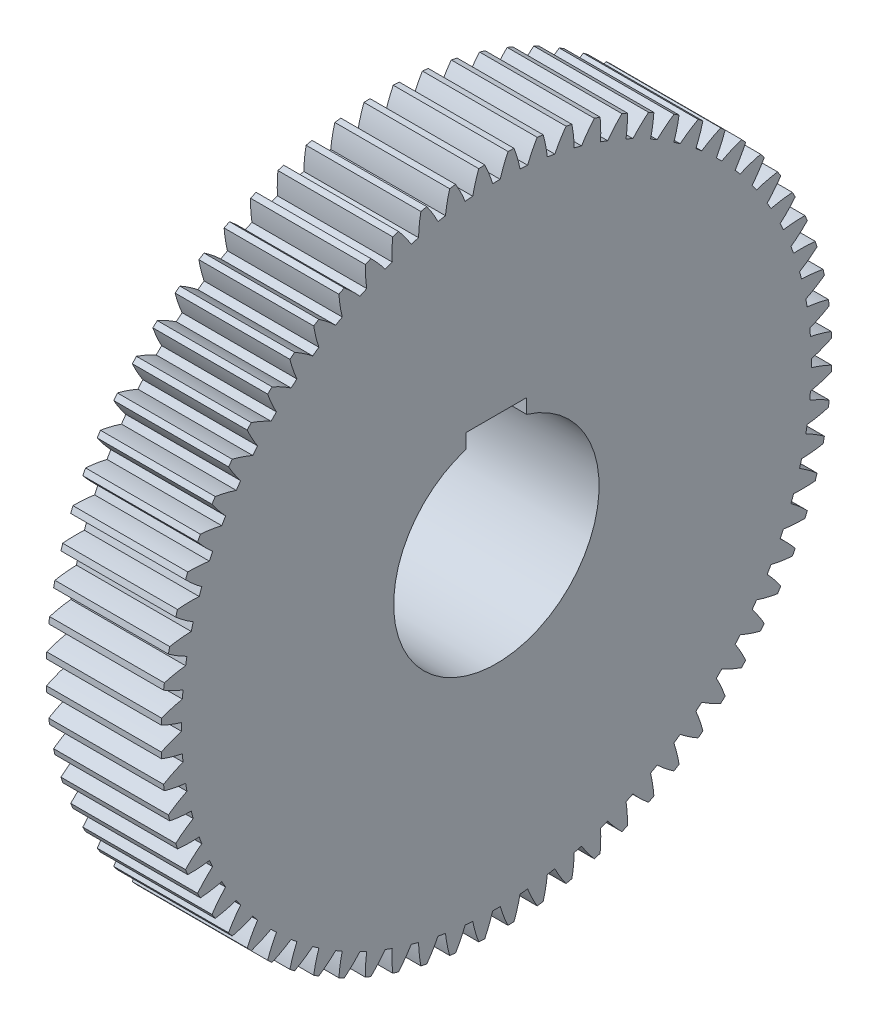
SolidWorks part; units mm, degrees
ref_plane "Plane1" through (0, 0, 0) normal (0, 0, 1) x (1, 0, 0)
ref_plane "Plane2" through (0, 0, 0) normal (0, 1, 0) x (1, 0, 0)
ref_plane "Plane3" through (0, 0, 0) normal (1, 0, 0) x (0, 0, -1)
sketch "HoldingSke" plane through (0, 0, 0) normal (0, 1, 0) x (1, 0, 0)
  line L0 (0, 0) -> (0.103, -0.317)
  line L1 (-15, 0) -> (100, 0) construction
  line L2 (0, 0) -> (-2.1039, 2.3779)
  line L3 (0, 0) -> (-11.863, 4.5341)
  line L4 (0, 0) -> (2.6687, 8.2133)
  line L5 (0, 0) -> (-58.0911, -21.6663)
  line L6 (0, 0) -> (-31.5006, -21.2535)
  line L7 (-2.1039, 2.3779) -> (11.2416, 62.9246)
  line L8 (-76.2, 54.61) -> (-71.3, 54.61)
  line L9 (-71.009, 38.7566) -> (-53.1078, 45.2721)
  line L10 (-76.2, 71.12) -> (104.1128, 71.12)
  line L11 (0, 0) -> (-38, 0)
  line L12 (-76.2, 101.6) -> (-76.093, 101.6)
  line L13 (24.9733, 27.94) -> (52.9518, 28.4284)
  line L14 (24.9733, 27.94) -> (24.9743, 27.94)
  line L15 (24.9733, 27.94) -> (100.4006, 29.5858)
  line L16 (-63.627, -3) -> (-12.827, -3)
  circle A0 centre (0, 0) radius 35
  circle A1 centre (0, 0) radius 42.5
  circle A2 centre (0, 0) radius 42.5
  circle A3 centre (0, 0) radius 35
  dimension "MHD" = 85
  dimension "Hub_dia" = 85
  dimension "Bore" = 70
  dimension "MBD" = 70
  dimension "Num_teeth" = 72
  dimension "Pitch" = 0.3333
  dimension "Overall_len" = 62
  dimension "Show_teeth" = 72
  dimension "Thickness" = 38
  dimension "OAL" = 62.0001
  dimension "T_dim" = 4.9
  dimension "Ap" = 20
  dimension "H" = 19.05
  dimension "Pitch_radius" = 180.3128
  dimension "Width" = 38
  dimension "Backlash" = 0.107
  dimension "Addendum_fac" = 1
  dimension "Dedendum_fac" = 1.25
  dimension "Clearance_fac" = 0.25
  dimension "Dedendum_add" = 0.001
  dimension "Module" = 3
sketch "BasProSke" plane through (0, 0, 0) normal (0, 1, 0) x (1, 0, 0)
  line L0 (-10, 0) -> (60, 0) construction
  line L1 (0, 0) -> (0, 111)
  line L2 (0, 0) -> (38, 0)
  line L3 (38, 0) -> (38, 111)
  line L4 (38, 111) -> (0, 111)
  dimension "Thickness" = 38
  dimension "Diameter" = 222
revolve "Base-Revolve" add sketch "BasProSke" angle 360 about L0
sketch "TooCutSke" plane through (0, 0, 0) normal (1, 0, 0) x (0, 0, -1)
  line L1 (0, 0) -> (0, 107) construction
  line L2 (0, 0) -> (-2.5433, 107.9701) construction
  line L3 (0, 0) -> (-9.4199, 215.7509) construction
  line L4 (-2.5433, 107.9701) -> (-4.7099, 107.8755) construction
  arc A0 (1.2601, 104.2414) -> (-1.2601, 104.2414) centre (0, 0) ccw
  arc A1 (3.8595, 110.9583) -> (-3.8595, 110.9583) centre (0, 0) ccw
  circle A2 centre (0, 0) radius 108 construction
  circle A3 centre (0, 0) radius 101.4868 construction
  arc A4 (-1.2601, 104.2414) -> (-3.8595, 110.9583) centre (-42.708, 92.063) ccw
  arc A5 (3.8595, 110.9583) -> (1.2601, 104.2414) centre (42.708, 92.063) ccw
  dimension "Root_dia" = 208.498
  dimension "Overcut_dia" = 222.0508
  dimension "Pitch_dia" = 216
  dimension "Base_dia" = 202.9736
  dimension "Flank_rad" = 43.2
  dimension "Half_ang" = 2.5
  dimension "Half_CT" = 2.1688
extrude "ToothCut" cut sketch "TooCutSke" along normal through all
fillet "Breaks" [suppressed] radius 0.06
fillet "RootFillets" [suppressed] radius 0.751
pattern_circular "TeethCuts" count 72 over 360 about axis through (0, 0, 0) along (1, 0, 0) of "ToothCut", "RootFillets", "Breaks"
sketch "HubNeaOneSke" plane through (0, 0, 0) normal (-1, 0, 0) x (0, 0, 1)
  circle A0 centre (0, 0) radius 42.5
  dimension "Diameter" = 85
extrude "HubNearOne" add sketch "HubNeaOneSke" along normal blind 24.0001
sketch "HubNeaBotSke" plane through (0, 0, 0) normal (-1, 0, 0) x (0, 0, 1)
  circle A0 centre (0, 0) radius 42.5
  dimension "Diameter" = 85
extrude "HubNearBoth" [suppressed] add sketch "HubNeaBotSke" along normal blind 12
ref_plane "FarPln" through (38, 0, 0) normal (1, 0, 0) x (0, 0, -1)
sketch "HubFarSke" plane through (38, 0, 0) normal (1, 0, 0) x (0, 0, -1)
  circle A0 centre (0, 0) radius 42.5
  dimension "Diameter" = 85
extrude "HubFar" [suppressed] add sketch "HubFarSke" along normal blind 12
sketch "BorSke" plane through (0, 0, 0) normal (1, 0, 0) x (0, 0, -1)
  circle A0 centre (0, 0) radius 34
  dimension "Diameter" = 68
extrude "Bore" cut sketch "BorSke" along normal mid plane 124.0001
sketch "KeySke" plane through (0, 0, 0) normal (1, 0, 0) x (0, 0, -1)
  line L0 (-10, 0) -> (-10, 37.3)
  line L1 (-10, 37.3) -> (10, 37.3)
  line L2 (10, 37.3) -> (10, 0)
  line L3 (0, 0) -> (0, 34) construction
  line L4 (-10, 0) -> (10, 0)
  dimension "Offset" = 37.3
  dimension "Width" = 20
extrude "Keyway" cut sketch "KeySke" along normal mid plane 124.0001
pattern_circular "Keyway2" [suppressed] count 2 every 90 about axis through (-10, 0, 0) along (1, 0, 0)
equation "' \"Module@HoldingSke\" = 6.35"
equation "' \"Num_teeth@HoldingSke\" = 12"
equation "' \"Ap@HoldingSke\" =  20"
equation "' \"Ap@HoldingSke\" = 20"
equation "' \"Width@HoldingSke\" = 0.5 * 25.4"
equation "' \"Hub_dia@HoldingSke\"= 1 * 25.4"
equation "' \"Hub_dia@HoldingSke\" = 1 * 25.4"
equation "' \"Overall_len@HoldingSke\" = 1.0 * 25.4"
equation "' \"Bore@HoldingSke\" = 0.75 * 25.4"
equation "' \"T_dim@HoldingSke\" = 0.1 * 25.4"
equation "' \"Width@KeySke\" = 0.25 * 25.4"
equation "' \"Show_teeth@HoldingSke\" = 13"
equation "' \"Backlash@HoldingSke\" = 0.009 * 25.4"
equation "' \"Addendum_fac@HoldingSke\" = 1.0"
equation "' \"Dedendum_fac@HoldingSke\" = 1.25"
equation "' \"Dedendum_add@HoldingSke\" = 0.00005 * 25.4"
equation "' \"Clearance_fac@HoldingSke\" = 0.25"
equation "\"Pitch@HoldingSke\" = 1 / \"Module@HoldingSke\""
equation "\"Overcut_dia@TooCutSke\" = (\"Num_teeth@HoldingSke\" + 2 * \"Addendum_fac@HoldingSke\") / \"Pitch@HoldingSke\" + 0.002 * 25.4"
equation "\"Pitch_dia@TooCutSke\" = \"Num_teeth@HoldingSke\" / \"Pitch@HoldingSke\""
equation "\"Base_dia@TooCutSke\" = \"Num_teeth@HoldingSke\" / \"Pitch@HoldingSke\" * cos((\"Ap@HoldingSke\"  * 3.14159265 / 180))"
equation "\"Root_dia@TooCutSke\" = (\"Num_teeth@HoldingSke\" + 2) / \"Pitch@HoldingSke\" - 2 * (\"Addendum_fac@HoldingSke\" + \"Dedendum_fac@HoldingSke\") / \"Pitch@HoldingSke\" - \"Dedendum_add@HoldingSke\" * 2"
equation "\"Half_ang@TooCutSke\" = 180 / \"Num_teeth@HoldingSke\""
equation "\"Half_CT@TooCutSke\" = \"Num_teeth@HoldingSke\" / \"Pitch@HoldingSke\" * sin((3.14159265 / 2 / \"Num_teeth@HoldingSke\")) / 2 - 7 * \"Backlash@HoldingSke\" / 4"
equation "\"Flank_rad@TooCutSke\" = \"Num_teeth@HoldingSke\" / \"Pitch@HoldingSke\" / 5"
equation "\"Radius@RootFillets\" = \"Clearance_fac@HoldingSke\" / \"Pitch@HoldingSke\" + \"Dedendum_add@HoldingSke\""
equation "\"Break_rad@Breaks\" = 0.02 / \"Pitch@HoldingSke\""
equation "\"Thickness@HoldingSke\" = \"Width@HoldingSke\""
equation "\"OAL@HoldingSke\" = \"Thickness@HoldingSke\""
equation "\"MHD@HoldingSke\" = (\"Num_teeth@HoldingSke\" + 2) / \"Pitch@HoldingSke\" - 2 * (\"Addendum_fac@HoldingSke\" + \"Dedendum_fac@HoldingSke\")  / \"Pitch@HoldingSke\" - \"Dedendum_add@HoldingSke\" * 2"
equation "\"MBD@HoldingSke\" = (\"Num_teeth@HoldingSke\" + 2) / \"Pitch@HoldingSke\" - 2 * (\"Addendum_fac@HoldingSke\" + \"Dedendum_fac@HoldingSke\")  / \"Pitch@HoldingSke\" - \"Dedendum_add@HoldingSke\" * 2 - 0.002 * 25.4"
equation "\"MHD@HoldingSke\" = ((sgn( \"MHD@HoldingSke\" - \"Hub_dia@HoldingSke\" )-1)*( \"MHD@HoldingSke\" - \"Hub_dia@HoldingSke\" ))/-2+ \"Hub_dia@HoldingSke\""
equation "\"MBD@HoldingSke\" = ((sgn( \"MBD@HoldingSke\" - \"Bore@HoldingSke\" )-1)*( \"MBD@HoldingSke\" - \"Bore@HoldingSke\" ))/-2+ \"Bore@HoldingSke\""
equation "\"OAL@HoldingSke\" = ((sgn( \"OAL@HoldingSke\" - \"Overall_len@HoldingSke\" )+1)*( \"OAL@HoldingSke\" - \"Overall_len@HoldingSke\" ))/2 + \"Overall_len@HoldingSke\" + 0.000002 * 25.4"
equation "\"Num_teeth@TeethCuts\" = int( \"Show_teeth@HoldingSke\" ) + 1"
equation "\"Num_teeth@TeethCuts\" = ((sgn( \"Num_teeth@TeethCuts\" - \"Num_teeth@HoldingSke\" )-1)*( \"Num_teeth@TeethCuts\" - \"Num_teeth@HoldingSke\" ))/-2+ \"Num_teeth@HoldingSke\""
equation "\"Num_teeth@TeethCuts\" = ((sgn( \"Num_teeth@TeethCuts\" - 2.0)+1)*( \"Num_teeth@TeethCuts\" - 2.0))/2 +2.0"
equation "\"Angle@TeethCuts\" = 360.0 / \"Num_teeth@HoldingSke\""
equation "\"Diameter@BasProSke\" = (\"Num_teeth@HoldingSke\" + 2 * \"Addendum_fac@HoldingSke\") / \"Pitch@HoldingSke\""
equation "\"Thickness@BasProSke\"  = \"Thickness@HoldingSke\""
equation "' \"Fillet_rad@BasProSke\" =  \"Thickness@HoldingSke\" * 0.05"
equation "' \"Fillet_rad@BasProSke\" = \"Thickness@HoldingSke\" * 0.05"
equation "\"MHD@HoldingSke\" = ((sgn( \"MHD@HoldingSke\" - \"Root_dia@TooCutSke\" )-1)*( \"MHD@HoldingSke\" - \"Root_dia@TooCutSke\" ))/-2+ \"Root_dia@TooCutSke\""
equation "\"Diameter@HubNeaOneSke\" = \"MHD@HoldingSke\""
equation "\"Length@HubNearOne\" = \"OAL@HoldingSke\" - \"Thickness@BasProSke\""
equation "\"Diameter@HubNeaBotSke\" = \"MHD@HoldingSke\""
equation "\"Length@HubNearBoth\" = ( \"OAL@HoldingSke\" - \"Thickness@BasProSke\" ) / 2.0"
equation "\"Thickness@FarPln\" = \"Thickness@BasProSke\""
equation "\"Diameter@HubFarSke\" = \"MHD@HoldingSke\""
equation "\"Length@HubFar\" = ( \"OAL@HoldingSke\" - \"Thickness@BasProSke\" ) / 2.0"
equation "\"D1@Bore\" = \"OAL@HoldingSke\" * 2.0"
equation "\"D1@Keyway\" = \"OAL@HoldingSke\" * 2.0"
